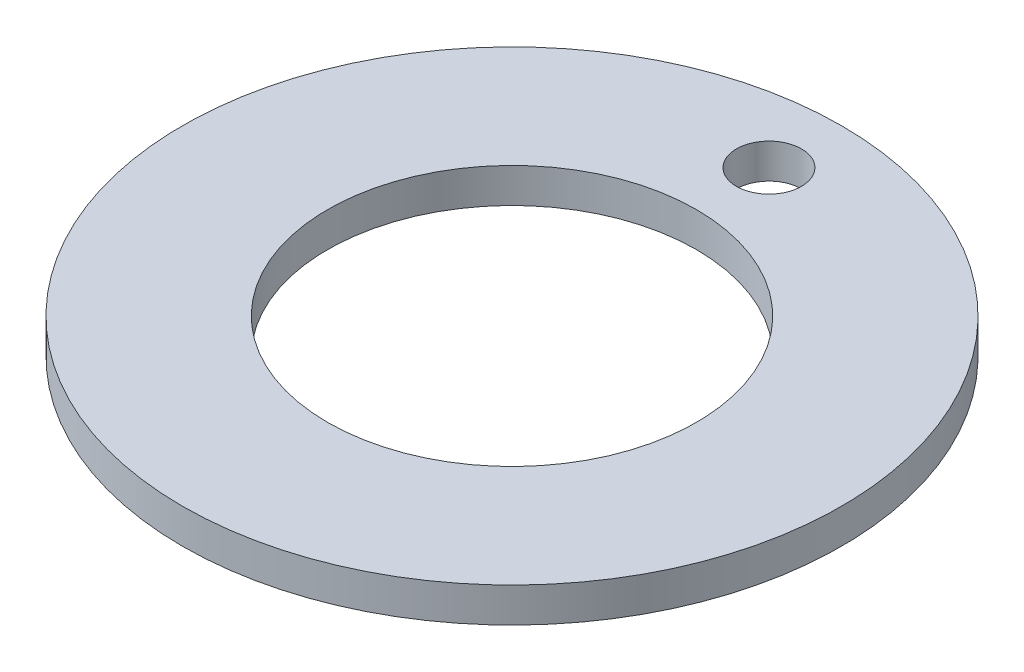
SolidWorks part; units mm, degrees
ref_plane "Front Plane" through (0, 0, 0) normal (0, 0, 1) x (1, 0, 0)
ref_plane "Top Plane" through (0, 0, 0) normal (0, 1, 0) x (1, 0, 0)
ref_plane "Right Plane" through (0, 0, 0) normal (1, 0, 0) x (0, 0, -1)
sketch "Sketch1" plane through (0, 0, 0) normal (0, 1, 0) x (1, 0, 0)
  line L0 (0, 48.26) -> (0, 27) construction
  circle A0 centre (0, 0) radius 48.26
  circle A1 centre (0, 0) radius 27
  circle A2 centre (0, 37.63) radius 4.7625
  point P8 (0, 37.63)
  dimension "D1" = 96.52
  dimension "D2" = 54
  dimension "D3" = 9.525
extrude "Boss-Extrude1" add sketch "Sketch1" along normal blind 5.08
